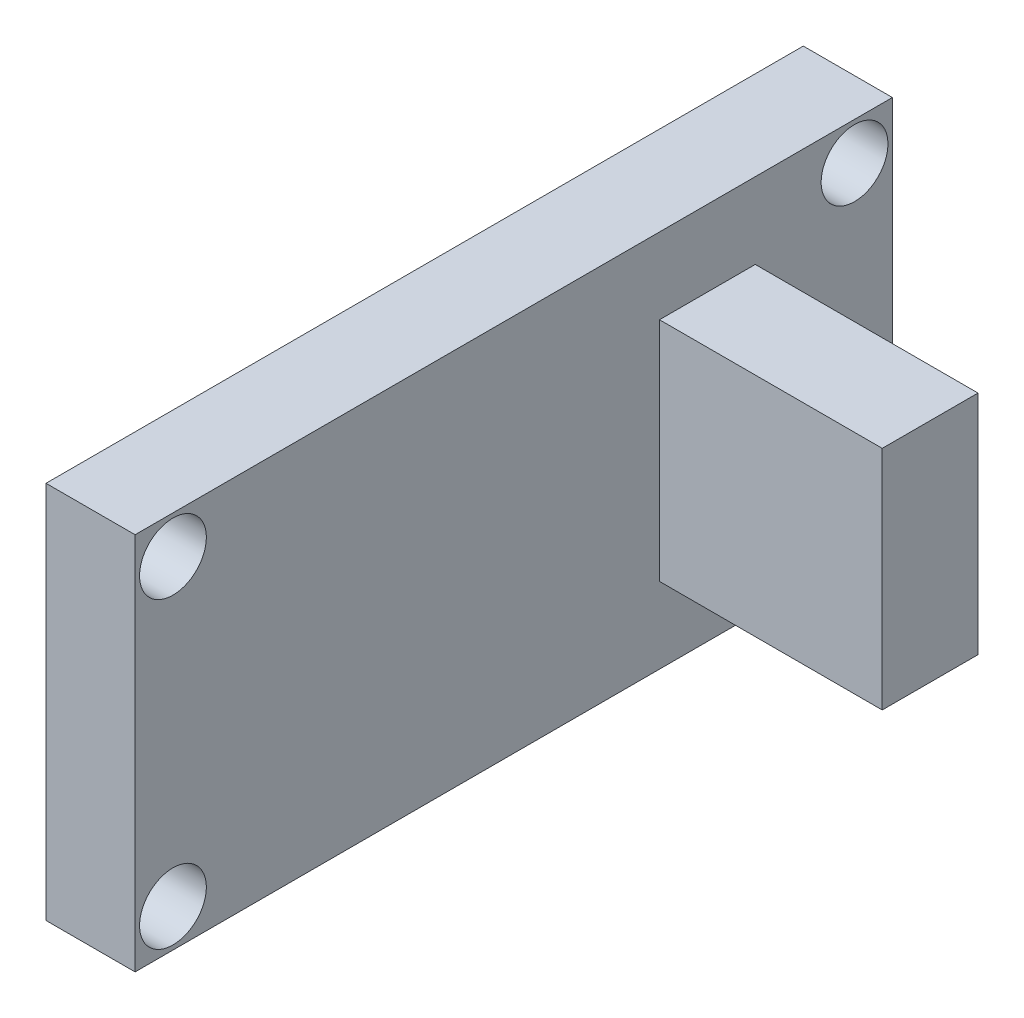
SolidWorks part; units mm, degrees
ref_plane "Front Plane" through (0, 0, 0) normal (0, 0, 1) x (1, 0, 0)
ref_plane "Top Plane" through (0, 0, 0) normal (0, 1, 0) x (1, 0, 0)
ref_plane "Right Plane" through (0, 0, 0) normal (1, 0, 0) x (0, 0, -1)
sketch "Sketch1" plane through (0, 0, 0) normal (1, 0, 0) x (0, 0, -1)
  line L1 (-17, 8.5) -> (17, 8.5)
  line L2 (-17, 8.5) -> (-17, -8.5)
  line L3 (-17, -8.5) -> (17, -8.5)
  line L4 (17, 8.5) -> (17, -8.5)
  line L5 (-17, 8.5) -> (17, -8.5) construction
  line L6 (-17, -8.5) -> (17, 8.5) construction
  point P0 (0, 0)
  dimension "D1" = 34
  dimension "D2" = 17
extrude "Boss-Extrude1" add sketch "Sketch1" along normal blind 4
sketch "Sketch2" plane through (4, 0, 0) normal (1, 0, 0) x (0, 0, -1)
  line L0 (17, 8.5) -> (-17, 8.5) construction
  line L1 (-17, 8.5) -> (-17, -8.5) construction
  line L2 (-17, -8.5) -> (17, -8.5) construction
  line L3 (0, 0) -> (0, 4.4678) construction
  circle A0 centre (-15.3, 6.8) radius 1.5
  circle A1 centre (-15.3, -6.8) radius 1.5
  circle A2 centre (15.3, -6.8) radius 1.5
  circle A3 centre (15.3, 6.8) radius 1.5
  point P17 (0, 0)
  point P18 (0, 0)
  dimension "D1" = 3
  dimension "D2" = 1.7
  dimension "D3" = 1.7
  dimension "D4" = 1.7
extrude "Cut-Extrude1" cut sketch "Sketch2" against normal through all
sketch "Sketch3" plane through (4, 0, 0) normal (1, 0, 0) x (0, 0, -1)
  line L1 (6.5438, -5.087) -> (10.8436, -5.087)
  line L2 (6.5438, -5.087) -> (6.5438, 5.087)
  line L3 (6.5438, 5.087) -> (10.8436, 5.087)
  line L4 (10.8436, -5.087) -> (10.8436, 5.087)
  line L5 (6.5438, -5.087) -> (10.8436, 5.087) construction
  line L6 (6.5438, 5.087) -> (10.8436, -5.087) construction
  point P0 (8.6937, 0)
extrude "Boss-Extrude2" add sketch "Sketch3" along normal blind 10
